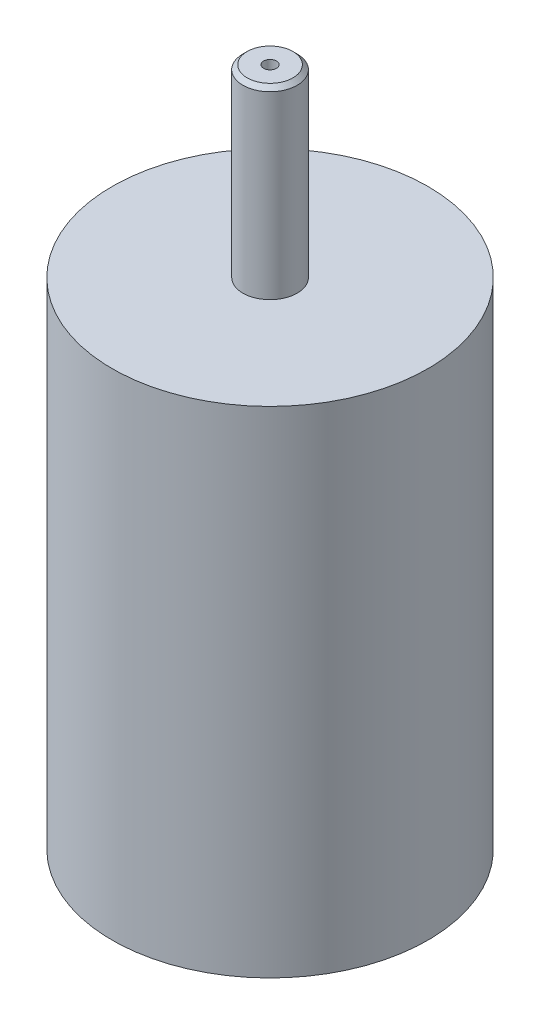
SolidWorks part; units mm, degrees
material "AISI 304"
ref_plane "Front Plane" through (0, 0, 0) normal (0, 0, 1) x (1, 0, 0)
ref_plane "Top Plane" through (0, 0, 0) normal (0, 1, 0) x (1, 0, 0)
ref_plane "Right Plane" through (0, 0, 0) normal (1, 0, 0) x (0, 0, -1)
sketch "Sketch1" plane through (0, 0, 0) normal (1, 0, 0) x (0, 0, -1)
  line L0 (0, -40.8) -> (0, 40.8)
  line L1 (0, 40.8) -> (3.18, 40.8)
  line L2 (3.18, 40.8) -> (3.18, 19.2)
  line L3 (3.18, 19.2) -> (18.5, 19.2)
  line L4 (18.5, 19.2) -> (18.5, -38.8)
  line L5 (18.5, -38.8) -> (3.18, -38.8)
  line L6 (3.18, -38.8) -> (3.18, -40.8)
  line L7 (3.18, -40.8) -> (0, -40.8)
  point P4 (0, 0)
  dimension "D1" = 58
  dimension "D2" = 60
  dimension "D3" = 3.18
  dimension "D4" = 21.6
  dimension "D5" = 18.5
revolve "Revolve1" add sketch "Sketch1" angle 360 about L0
chamfer "Chamfer1" distance 0.5 angle 45 1 edges at (0, 40.8, -3.18)
sketch "Sketch2" plane through (0, 40.8, 0) normal (0, 1, 0) x (1, 0, 0)
  line L0 (-2.5936, 1.84) -> (2.5936, 1.84)
  circle A0 centre (0, 0) radius 3.18 construction
  arc A1 (2.5936, 1.84) -> (-2.5936, 1.84) centre (0, 0) ccw
  dimension "D1" = 1.84
extrude "Cut-Extrude1" [suppressed] cut sketch "Sketch2" against normal blind 15
sketch "Sketch3" plane through (0, 40.8, 0) normal (0, 1, 0) x (1, 0, 0)
  circle A0 centre (0, 0) radius 0.75
  dimension "D1" = 1.5
extrude "Cut-Extrude2" cut sketch "Sketch3" against normal through all
